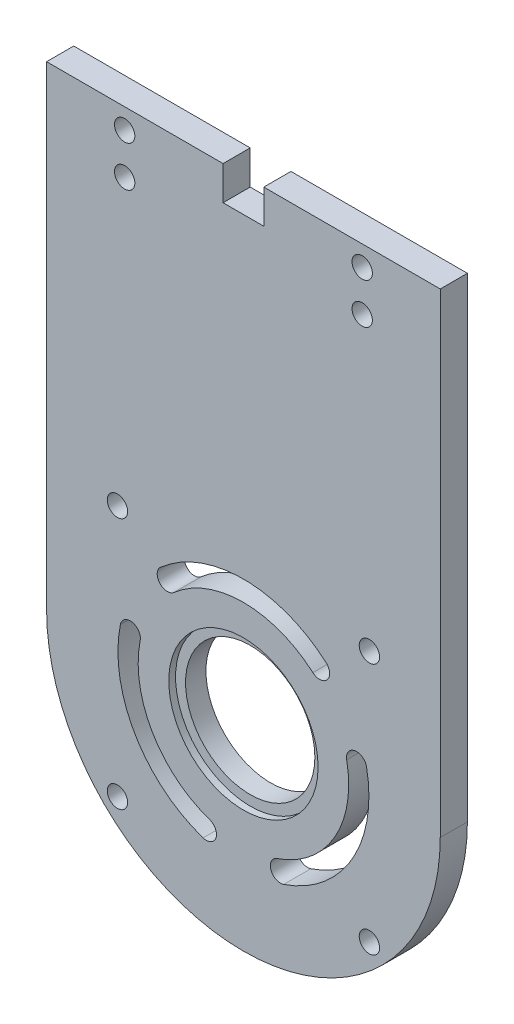
SolidWorks part; units mm, degrees
ref_plane "前视基准面" through (0, 0, 0) normal (0, 0, 1) x (1, 0, 0)
ref_plane "上视基准面" through (0, 0, 0) normal (0, 1, 0) x (1, 0, 0)
ref_plane "右视基准面" through (0, 0, 0) normal (1, 0, 0) x (0, 0, -1)
other "Configuration Table"
sketch "草图1" plane through (0, 0, 0) normal (0, 0, 1) x (1, 0, 0)
  line L0 (-29, 6) -> (29, 6)
  line L1 (29, 6) -> (29, -64)
  line L2 (0, 0) -> (0, 6) construction
  line L3 (-29, 6) -> (-29, -64)
  line L4 (-29, -64) -> (29, -64) construction
  line L5 (0, 3) -> (-17.5, 3) construction
  line L6 (0, -64) -> (18.5616, -82.5616) construction
  line L7 (-17.5, 3) -> (-17.5, -3) construction
  arc A0 (-29, -64) -> (29, -64) centre (0, -64) ccw
  circle A1 centre (0, -64) radius 9.525
  circle A2 centre (-17.5, 3) radius 1.5
  circle A3 centre (17.5, 3) radius 1.5
  circle A4 centre (0, -64) radius 54 construction
  circle A5 centre (18.5616, -82.5616) radius 1.5
  circle A6 centre (-18.5616, -82.5616) radius 1.5
  circle A7 centre (-18.5616, -45.4384) radius 1.5
  circle A8 centre (18.5616, -45.4384) radius 1.5
  circle A9 centre (-17.5, -3) radius 1.5
  circle A10 centre (17.5, -3) radius 1.5
  point P27 (0, -64)
  dimension "D1" = 19.05
  dimension "D4" = 35
  dimension "D5" = 3
  dimension "D6" = 108
  dimension "D8" = 3
  dimension "D10" = 26.25
  dimension "D2" = 6
  dimension "D3" = 58
  dimension "D7" = 70
  dimension "D9" = 45
  dimension "D13" = 6
  dimension "D12" = 2
  dimension "D11" = 4
extrude "凸台-拉伸1" add sketch "草图1" along normal blind 4 contours L3 A0 L1 L0 A1 A2 A3
sketch "草图2" plane through (0, 0, 4) normal (0, 0, 1) x (1, 0, 0)
  line L0 (-29, 6) -> (29, 6) construction
  line L1 (-3, 6) -> (3, 6)
  line L2 (-3, 6) -> (-3, 1)
  line L3 (-3, 1) -> (3, 1)
  line L4 (3, 6) -> (3, 1)
  line L5 (0, 0) -> (0, 6) construction
  dimension "D1" = 6
  dimension "D2" = 5
extrude "切除-拉伸1" cut sketch "草图2" against normal through all
sketch "草图3" plane through (0, 0, 4) normal (0, 0, 1) x (1, 0, 0)
  line L0 (0, -47) -> (0, -64) construction
  line L1 (0, -64) -> (-11.2136, -51.2228) construction
  arc A0 (-11.2136, -51.2228) -> (11.2136, -51.2228) centre (0, -64) cw construction
  arc A1 (12.1961, -50.1033) -> (-12.1961, -50.1033) centre (0, -64) ccw
  arc A2 (10.231, -52.3424) -> (-10.231, -52.3424) centre (0, -64) ccw
  arc A3 (10.231, -52.3424) -> (12.1961, -50.1033) centre (11.2136, -51.2228) ccw
  arc A4 (-12.1961, -50.1033) -> (-10.231, -52.3424) centre (-11.2136, -51.2228) ccw
  arc A5 (16.6721, -60.6773) -> (5.4585, -80.0998) centre (0, -64) cw construction
  arc A6 (5.9368, -81.5105) -> (18.133, -60.3862) centre (0, -64) ccw
  arc A7 (4.9803, -78.6891) -> (15.2113, -60.9685) centre (0, -64) ccw
  arc A8 (4.9803, -78.6891) -> (5.9368, -81.5105) centre (5.4585, -80.0998) ccw
  arc A9 (18.133, -60.3862) -> (15.2113, -60.9685) centre (16.6721, -60.6773) ccw
  arc A10 (-5.4585, -80.0998) -> (-16.6721, -60.6773) centre (0, -64) cw construction
  arc A11 (-18.133, -60.3862) -> (-5.9368, -81.5105) centre (0, -64) ccw
  arc A12 (-15.2113, -60.9685) -> (-4.9803, -78.6891) centre (0, -64) ccw
  arc A13 (-15.2113, -60.9685) -> (-18.133, -60.3862) centre (-16.6721, -60.6773) ccw
  arc A14 (-5.9368, -81.5105) -> (-4.9803, -78.6891) centre (-5.4585, -80.0998) ccw
  point P0 (0, -64)
  point P1 (0, -47)
  point P10 (14.7224, -72.5)
  point P21 (-14.7224, -72.5)
  dimension "D2" = 17
  dimension "D1" = 3
extrude "切除-拉伸2" cut sketch "草图3" against normal blind 10
sketch "草图4" plane through (0, 0, 4) normal (0, 0, 1) x (1, 0, 0)
  circle A0 centre (0, -64) radius 11
  dimension "D1" = 22
extrude "切除-拉伸3" cut sketch "草图4" against normal blind 1
